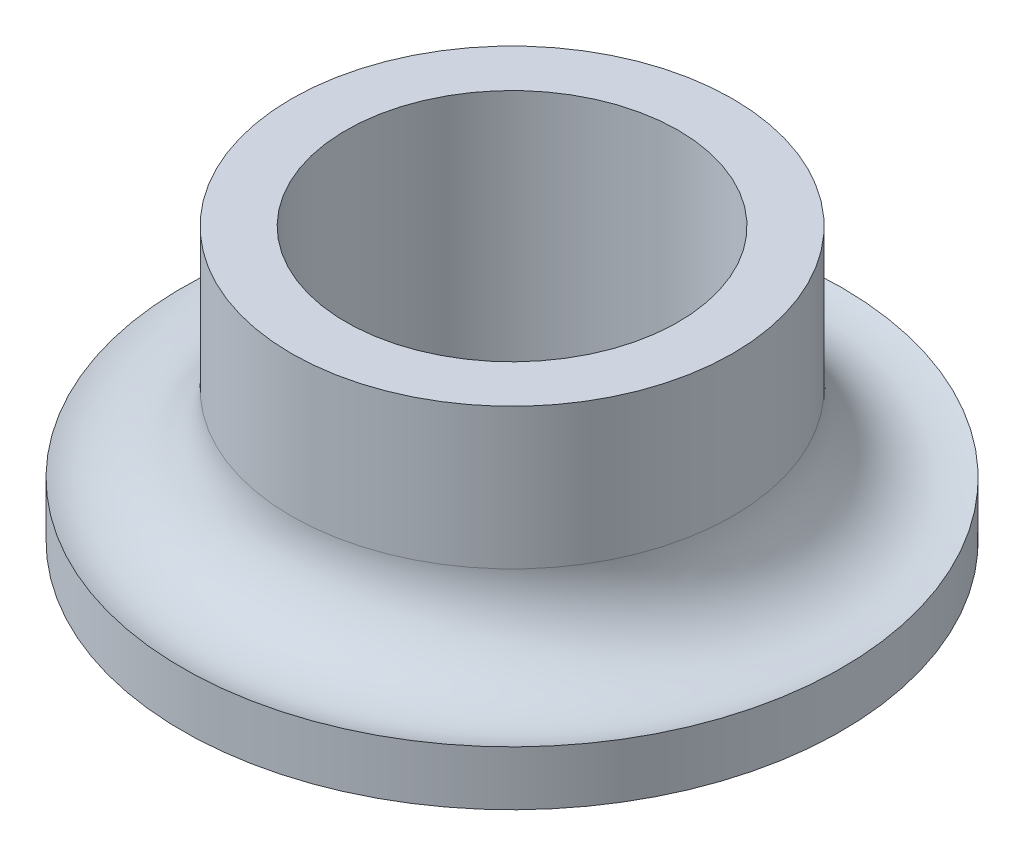
SolidWorks part; units mm, degrees
ref_plane "Plan de face" through (0, 0, 0) normal (0, 0, 1) x (1, 0, 0)
ref_plane "Plan de dessus" through (0, 0, 0) normal (0, 1, 0) x (1, 0, 0)
ref_plane "Plan de droite" through (0, 0, 0) normal (1, 0, 0) x (0, 0, -1)
sketch "Esquisse1" plane through (0, 0, 0) normal (0, 0, 1) x (1, 0, 0)
  line L0 (-4.05, 5) -> (-4.05, 2.4142)
  line L2 (-6.05, 1) -> (-6.05, 0)
  line L3 (-6.05, 0) -> (-3.05, 0)
  line L4 (0, 0) -> (0, 4.2065) construction
  line L5 (-4.05, 5) -> (-3.05, 5)
  line L6 (-3.05, 5) -> (-3.05, 0)
  line L7 (-3.05, 0) -> (0, 0) construction
  arc A0 (-4.05, 2.4142) -> (-6.05, 1) centre (-5.55, 2.4142) cw
  dimension "D6" = 1.5
  dimension "D1" = 3.05
  dimension "D2" = 1
  dimension "D3" = 1
  dimension "D4" = 5
  dimension "D5" = 3
revolve "Révolution1" add sketch "Esquisse1" angle 360 about L4
